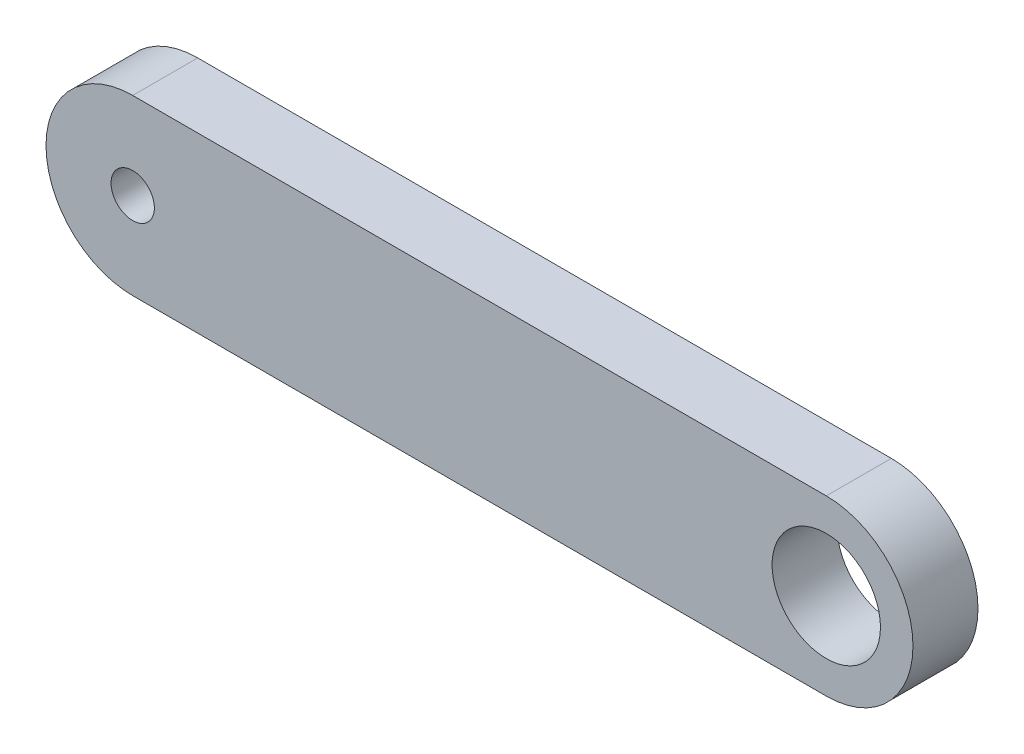
SolidWorks part; units mm, degrees
ref_plane "Front Plane" through (0, 0, 0) normal (0, 0, 1) x (1, 0, 0)
ref_plane "Top Plane" through (0, 0, 0) normal (0, 1, 0) x (1, 0, 0)
ref_plane "Right Plane" through (0, 0, 0) normal (1, 0, 0) x (0, 0, -1)
sketch "Sketch1" plane through (0, 0, 0) normal (0, 0, 1) x (1, 0, 0)
  line L0 (0, -55) -> (0, 55) construction
  line L1 (-16, 4) -> (16, 4)
  line L3 (-16, -4) -> (16, -4)
  line L5 (-16, 4) -> (16, -4) construction
  line L6 (-16, -4) -> (16, 4) construction
  arc A0 (-16, 4) -> (-16, -4) centre (-16, 0) ccw
  arc A1 (16, 4) -> (16, -4) centre (16, 0) cw
  circle A2 centre (-16, 0) radius 1
  circle A4 centre (16, 0) radius 2.5
  point P0 (0, 0)
  point P9 (-20, 0)
  point P10 (20, 0)
  dimension "D1" = 2
  dimension "D3" = 4
  dimension "D4" = 5
  dimension "D2" = 40
extrude "Boss-Extrude1" add sketch "Sketch1" along normal blind 3
